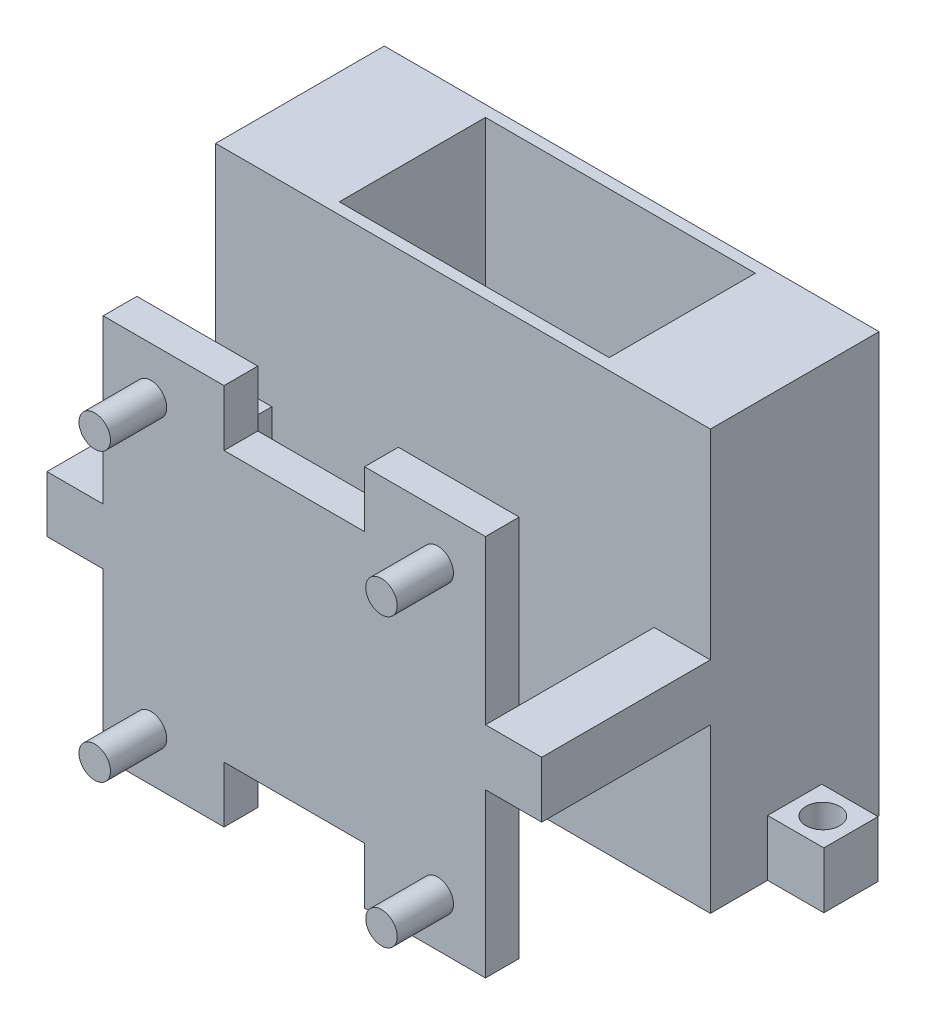
SolidWorks part; units mm, degrees
ref_plane "Front Plane" through (0, 0, 0) normal (0, 0, 1) x (1, 0, 0)
ref_plane "Top Plane" through (0, 0, 0) normal (0, 1, 0) x (1, 0, 0)
ref_plane "Right Plane" through (0, 0, 0) normal (1, 0, 0) x (0, 0, -1)
sketch "Sketch1" plane through (0, 0, 0) normal (0, 0, 1) x (1, 0, 0)
  line L0 (0, 0) -> (0, -34)
  line L1 (0, -34) -> (34, -34)
  line L2 (34, -34) -> (34, 0)
  line L3 (34, 0) -> (0, 0)
  dimension "D1" = 34
  dimension "D2" = 34
extrude "Boss-Extrude1" add sketch "Sketch1" along normal blind 3
sketch "Sketch2" plane through (0, 0, 0) normal (0, 0, -1) x (-1, 0, 0)
  line L0 (-17, 0) -> (-17, -34) construction
  line L1 (-34, 0) -> (0, 0) construction
  line L2 (0, -34) -> (-34, -34) construction
  line L3 (-34, -17) -> (0, -17) construction
  line L4 (-34, -34) -> (-34, 0) construction
  line L5 (0, 0) -> (0, -34) construction
  line L6 (-23.25, -5) -> (-10.75, -5)
  line L7 (-10.75, -5) -> (-10.75, 0)
  line L8 (-10.75, 0) -> (-23.25, 0)
  line L9 (-23.25, -5) -> (-23.25, 0)
  line L10 (-10.75, -29) -> (-10.75, -34)
  line L11 (-23.25, -29) -> (-10.75, -29)
  line L12 (-23.25, -29) -> (-23.25, -34)
  line L13 (-10.75, -34) -> (-23.25, -34)
  point P17 (-17, -5)
  dimension "D1" = 6.25
  dimension "D2" = 5
extrude "Cut-Extrude1" cut sketch "Sketch2" against normal through all contours L8 L9 L6 L7 | L10 L13 L12 L11
sketch "Sketch3" plane through (0, 0, 0) normal (0, 0, -1) x (-1, 0, 0)
  line L0 (-34, -34) -> (-34, 0) construction
  line L1 (-34, 0) -> (-23.25, 0) construction
  line L2 (-17, -5) -> (-17, -29) construction
  line L3 (-23.25, -5) -> (-10.75, -5) construction
  line L4 (-23.25, -29) -> (-10.75, -29) construction
  line L5 (-34, -17) -> (0, -17) construction
  line L6 (0, 0) -> (0, -34) construction
  circle A0 centre (-29.75, -4.25) radius 1.4
  circle A2 centre (-4.25, -4.25) radius 1.4
  circle A3 centre (-4.25, -29.75) radius 1.4
  circle A4 centre (-29.75, -29.75) radius 1.4
  dimension "D1" = 4.25
  dimension "D2" = 4.25
  dimension "D3" = 25.5
  dimension "D4" = 2.8
  dimension "D5" = 2.8
  dimension "D6" = 2.8
sketch "Sketch25" plane through (34, 0, 0) normal (1, 0, 0) x (0, 0, -1)
  line L0 (-3, -17) -> (0, -17) construction
  line L1 (-3, -34) -> (-3, 0) construction
  line L2 (0, -34) -> (0, 0) construction
  line L3 (-3, -17) -> (-3, -14.5)
  line L4 (-3, -14.5) -> (12, -14.5)
  line L11 (12, -14.5) -> (12, -19.5)
  line L12 (-3, -17) -> (-3, -19.5)
  line L13 (-3, -19.5) -> (12, -19.5)
  dimension "D1" = 2.5
  dimension "D2" = 15
  dimension "D4" = 5
extrude "Boss-Extrude2" add sketch "Sketch25" along normal blind 5
sketch "Sketch31" plane through (0, 0, 0) normal (0, 0, -1) x (-1, 0, 0)
  line L0 (-17, -5) -> (-17, -29) construction
  line L1 (-23.25, -5) -> (-10.75, -5) construction
  line L2 (-23.25, -29) -> (-10.75, -29) construction
extrude "Boss-Extrude3" add sketch "Sketch3" against normal blind 8
sketch "Sketch33" plane through (0, 0, 0) normal (-1, 0, 0) x (0, 0, 1)
  line L0 (3, -14.5) -> (-12, -14.5)
  line L1 (-12, -14.5) -> (-12, -19.5)
  line L2 (-12, -19.5) -> (3, -19.5)
  line L3 (3, -19.5) -> (3, -14.5)
  dimension "D1" = 15
extrude "Boss-Extrude4" add sketch "Sketch33" along normal blind 5
sketch "Sketch35" plane through (0, 0, -12) normal (0, 0, -1) x (-1, 0, 0)
  line L6 (-39, -17) -> (-39, 3.2777)
  line L7 (-39, -19.5) -> (-39, -14.5) construction
  line L8 (-39, 3.2777) -> (5, 3.2777)
  line L9 (5, 3.2777) -> (5, -17)
  line L10 (5, -14.5) -> (5, -19.5) construction
  line L11 (5, -17) -> (5, -34.026)
  line L12 (5, -34.026) -> (-39, -34.026)
  line L13 (-39, -34.026) -> (-39, -17)
  dimension "D1" = 44
  dimension "D2" = 44
  dimension "D3" = 37.3037
extrude "Boss-Extrude6" add sketch "Sketch35" along normal blind 15
sketch "Sketch36" plane through (0, 3.2777, 0) normal (0, 1, 0) x (1, 0, 0)
  line L0 (17, 27) -> (17, 12) construction
  line L1 (-5, 27) -> (39, 27) construction
  line L2 (-5, 12) -> (39, 12) construction
  line L3 (5, 26) -> (29, 26)
  line L4 (29, 26) -> (29, 13)
  line L5 (29, 13) -> (5, 13)
  line L6 (5, 26) -> (5, 13)
  point P11 (17, 13)
  point P12 (17, 26)
  dimension "D1" = 12
  dimension "D2" = 13
  dimension "D3" = 1
extrude "Cut-Extrude2" cut sketch "Sketch36" against normal blind 19.5
sketch "Sketch38" plane through (0, -34.026, 0) normal (0, -1, 0) x (-1, 0, 0)
  line L0 (-39, 19.5) -> (5, 19.5) construction
  line L1 (-39, 27) -> (-39, 12) construction
  line L2 (5, 27) -> (5, 12) construction
  line L3 (-39, 21.9101) -> (-39, 17.0899)
  line L4 (-39, 17.0899) -> (-44, 17.0899)
  line L5 (-44, 17.0899) -> (-44, 19.5899)
  line L6 (-39, 21.9101) -> (-44, 21.9101)
  line L7 (-44, 21.9101) -> (-44, 19.4101)
  line L8 (-17, 12) -> (-17, 27) construction
  line L9 (-39, 12) -> (5, 12) construction
  line L10 (-39, 27) -> (5, 27) construction
  line L11 (5, 21.9101) -> (5, 17.0899)
  line L12 (5, 21.9101) -> (10, 21.9101)
  line L13 (10, 21.9101) -> (10, 19.4101)
  line L14 (10, 17.0899) -> (10, 19.5899)
  line L15 (5, 17.0899) -> (10, 17.0899)
  line M9 (5, 12) -> (5, 27)
  line M11 (-39, 27) -> (-39, 12)
  dimension "D1" = 5
  dimension "D2" = 2.5
extrude "Boss-Extrude7" add sketch "Sketch38" against normal blind 5 contours L15 L14 L13 L12 M9 | L6 L7 L5 L4 M11
sketch "Sketch39" plane through (0, -29.026, 0) normal (0, 1, 0) x (1, 0, 0)
  line L0 (-7.5, 21.9101) -> (-7.5, 17.0899) construction
  line L1 (-5, 21.9101) -> (-10, 21.9101) construction
  line L2 (-5, 17.0899) -> (-10, 17.0899) construction
  line L3 (41.5, 21.9101) -> (41.5, 17.0899) construction
  line L4 (39, 21.9101) -> (44, 21.9101) construction
  line L5 (39, 17.0899) -> (44, 17.0899) construction
  circle A0 centre (-7.5, 19.5) radius 1.5
  circle A1 centre (41.5, 19.5) radius 1.5
extrude "Cut-Extrude3" cut sketch "Sketch39" against normal through all
